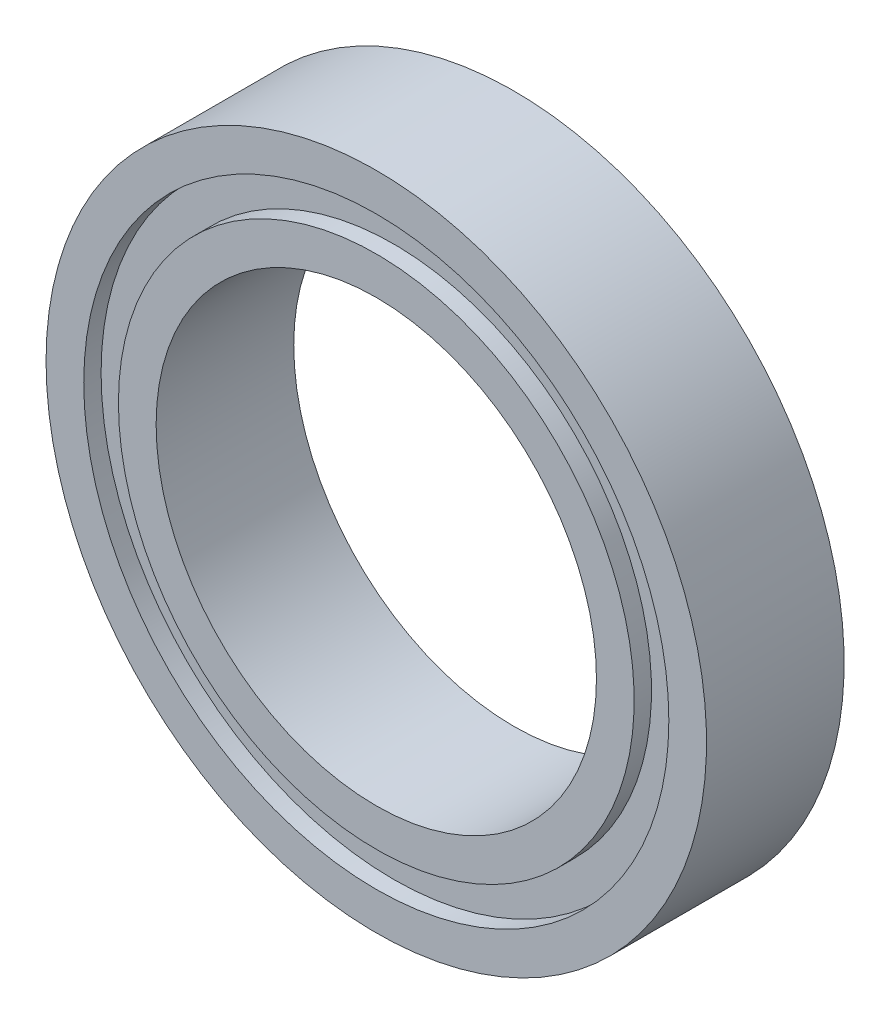
SolidWorks part; units mm, degrees
ref_plane "Front Plane" through (0, 0, 0) normal (0, 0, 1) x (1, 0, 0)
ref_plane "Top Plane" through (0, 0, 0) normal (0, 1, 0) x (1, 0, 0)
ref_plane "Right Plane" through (0, 0, 0) normal (1, 0, 0) x (0, 0, -1)
sketch "Sketch1" plane through (0, 0, 0) normal (0, 1, 0) x (1, 0, 0)
  line L0 (0, 1.9844) -> (0, 0) construction
  line L1 (-6.35, -1.9844) -> (-6.35, 1.9844)
  line L2 (-6.35, 1.9844) -> (-7.4375, 1.9844)
  line L3 (-7.4375, 1.9844) -> (-7.4375, 1.4844)
  line L4 (-7.4375, 1.4844) -> (-8.4375, 1.4844)
  line L5 (-8.4375, 1.4844) -> (-8.4375, 1.9844)
  line L6 (-8.4375, 1.9844) -> (-9.525, 1.9844)
  line L7 (-9.525, 1.9844) -> (-9.525, -1.9844)
  line L8 (-9.525, 0) -> (-6.35, 0) construction
  line L9 (-8.4375, -1.9844) -> (-9.525, -1.9844)
  line L10 (-8.4375, -1.4844) -> (-8.4375, -1.9844)
  line L11 (-7.4375, -1.4844) -> (-8.4375, -1.4844)
  line L12 (-7.4375, -1.9844) -> (-7.4375, -1.4844)
  line L13 (-6.35, -1.9844) -> (-7.4375, -1.9844)
  dimension "D1" = 19.05
  dimension "D2" = 12.7
  dimension "D3" = 1
  dimension "D4" = 0.5
  dimension "D5" = 3.9688
revolve "Revolve1" add sketch "Sketch1" angle 360 about L0
